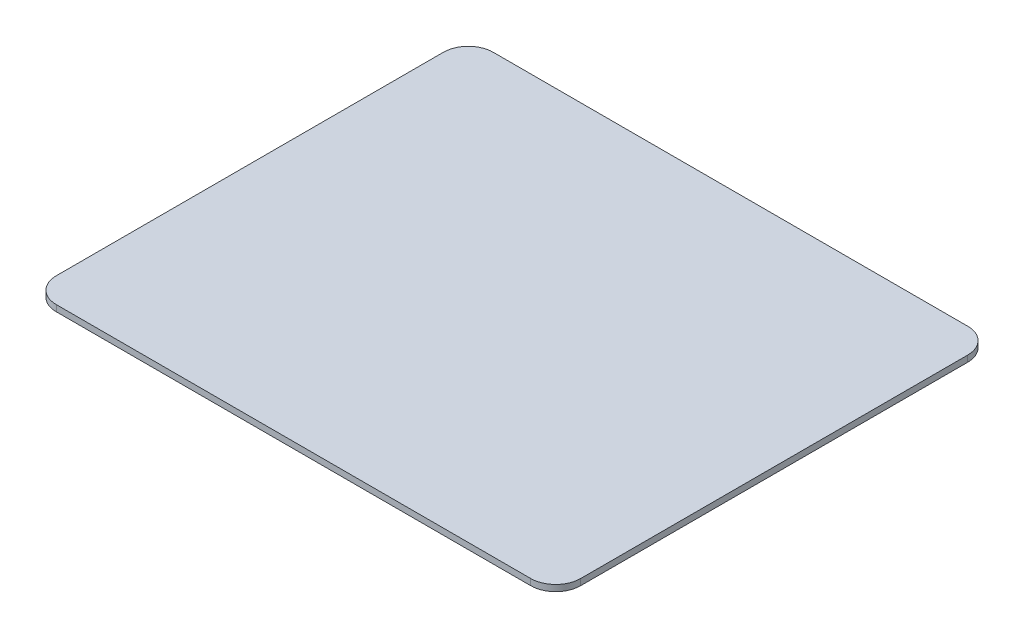
SolidWorks part; units mm, degrees
ref_plane "前视基准面" through (0, 0, 0) normal (0, 0, 1) x (1, 0, 0)
ref_plane "上视基准面" through (0, 0, 0) normal (0, 1, 0) x (1, 0, 0)
ref_plane "右视基准面" through (0, 0, 0) normal (1, 0, 0) x (0, 0, -1)
other "Configuration Table"
sketch "草图1" plane through (0, 0, 0) normal (0, 1, 0) x (1, 0, 0)
  line L1 (-210, -175) -> (210, -175)
  line L2 (-210, -175) -> (-210, 175)
  line L3 (-210, 175) -> (210, 175)
  line L4 (210, -175) -> (210, 175)
  line L5 (-210, -175) -> (210, 175) construction
  line L6 (-210, 175) -> (210, -175) construction
  point P0 (0, 0)
  dimension "D1" = 420
  dimension "D2" = 350
extrude "凸台-拉伸1" add sketch "草图1" along normal blind 5
fillet "圆角1" radius 20 4 edges at (210, 2.5, 175) (210, 2.5, -175) (-210, 2.5, -175) (-210, 2.5, 175)
